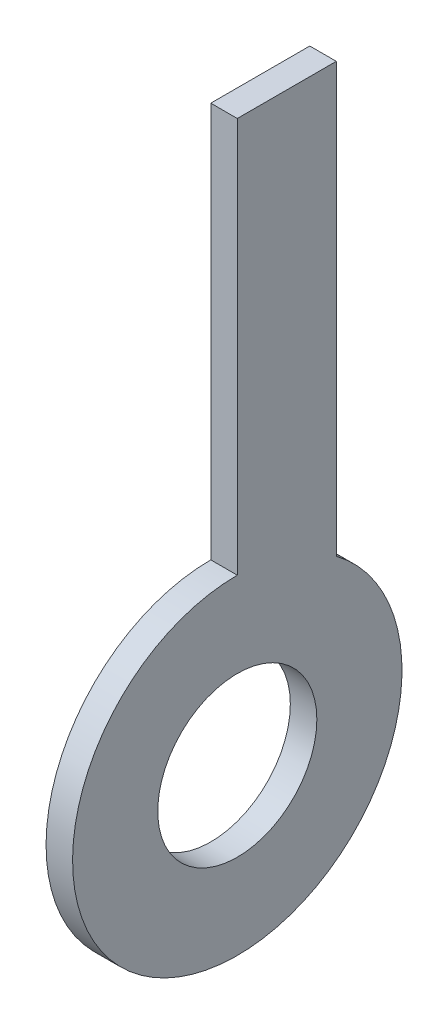
SolidWorks part; units mm, degrees
ref_plane "前视基准面" through (0, 0, 0) normal (0, 0, 1) x (1, 0, 0)
ref_plane "上视基准面" through (0, 0, 0) normal (0, 1, 0) x (1, 0, 0)
ref_plane "右视基准面" through (0, 0, 0) normal (1, 0, 0) x (0, 0, -1)
other "Configuration Table"
sketch "草图1" plane through (0, 0, 0) normal (1, 0, 0) x (0, 0, -1)
  line L0 (0, 12.4206) -> (0, 42.2489)
  line L1 (0, 42.2489) -> (7.4661, 42.2489)
  line L2 (7.4661, 42.2489) -> (7.4661, 9.9261)
  circle A0 centre (0, 0) radius 6
  arc A1 (0, 12.4206) -> (7.4661, 9.9261) centre (0, 0) ccw
  dimension "D1" = 12
extrude "凸台-拉伸1" add sketch "草图1" along normal blind 2
